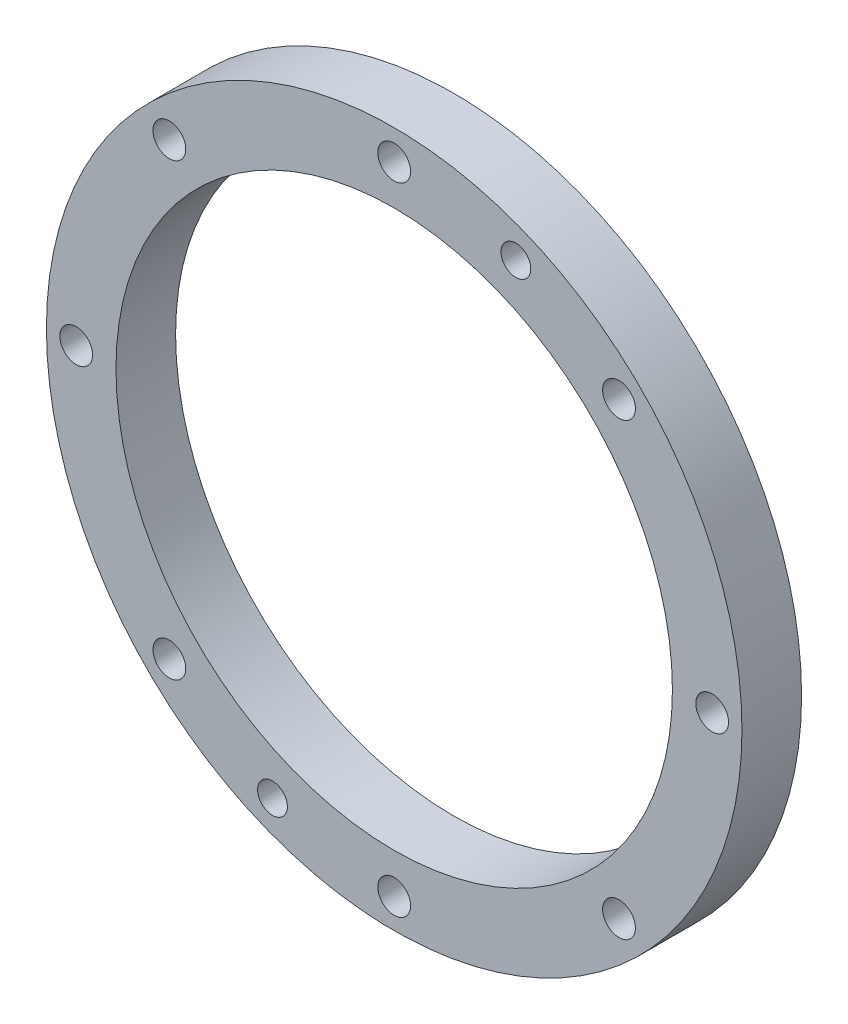
SolidWorks part; units mm, degrees
material "1.0503 (C45)"
ref_plane "Front Plane" through (0, 0, 0) normal (0, 0, 1) x (1, 0, 0)
ref_plane "Top Plane" through (0, 0, 0) normal (0, 1, 0) x (1, 0, 0)
ref_plane "Right Plane" through (0, 0, 0) normal (1, 0, 0) x (0, 0, -1)
sketch "Sketch1" plane through (0, 0, 0) normal (0, 1, 0) x (1, 0, 0)
  line L0 (56, 19.5) -> (70, 19.5)
  line L1 (70, 19.5) -> (70, 7.5)
  line L2 (70, 7.5) -> (56, 7.5)
  line L3 (56, 7.5) -> (56, 19.5)
  line L4 (0, -150) -> (0, 150) construction
revolve "REV_Interstage_Spacer" add sketch "Sketch1" angle 360 about L4
sketch "Sketch2" plane through (0, 0, 0) normal (0, 0, 1) x (1, 0, 0)
  circle A0 centre (64, 0) radius 3.3
  circle A1 centre (45.2548, 45.2548) radius 3.3
  circle A2 centre (0, 64) radius 3.3
  circle A3 centre (-45.2548, 45.2548) radius 3.3
  circle A4 centre (-64, 0) radius 3.3
  circle A5 centre (-45.2548, -45.2548) radius 3.3
  circle A6 centre (0, -64) radius 3.3
  circle A7 centre (45.2548, -45.2548) radius 3.3
  circle A8 centre (24.4917, 59.1283) radius 3
  circle A9 centre (-24.4917, -59.1283) radius 3
extrude "CUT_8xTie_D6.6_2xDowel_D6_PCD128" cut sketch "Sketch2" along normal mid plane 300
